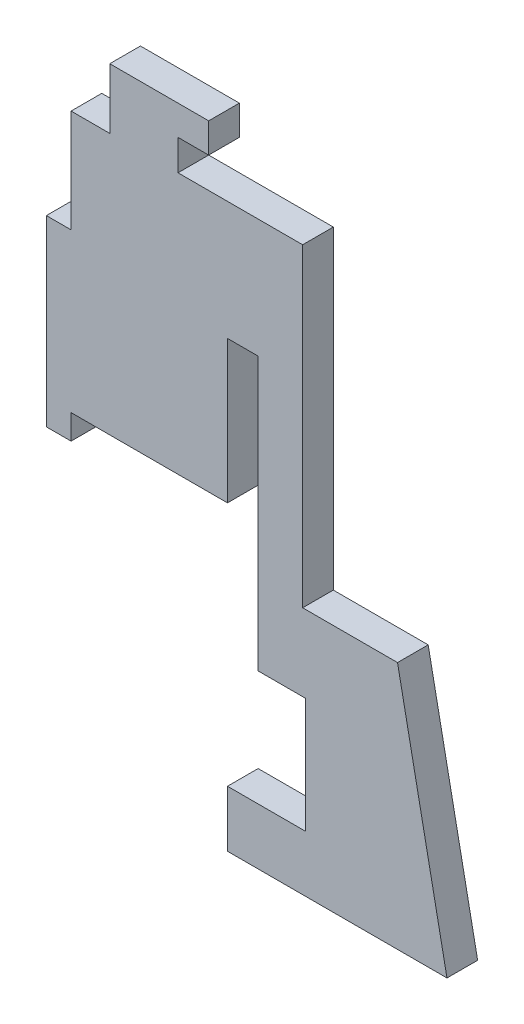
SolidWorks part; units mm, degrees
ref_plane "Front Plane" through (0, 0, 0) normal (0, 0, 1) x (1, 0, 0)
ref_plane "Top Plane" through (0, 0, 0) normal (0, 1, 0) x (1, 0, 0)
ref_plane "Right Plane" through (0, 0, 0) normal (1, 0, 0) x (0, 0, -1)
sketch "Sketch1" plane through (0, 0, 0) normal (0, 0, 1) x (1, 0, 0)
  line L0 (-72.5, 31.1) -> (-70, 31.1)
  line L1 (-54.19, 8.7934) -> (-54.19, 3.1)
  line L2 (-72.5, 31.1) -> (-72.5, 49.6)
  line L3 (-70, 60) -> (-66.09, 60)
  line L4 (-54.19, 33.6) -> (-54.19, 48)
  line L5 (-70, 31.1) -> (-70, 33.6)
  line L6 (-70, 33.6) -> (-54.19, 33.6)
  line L7 (-59.19, 63.1) -> (-56.09, 63.1)
  line L8 (-59.19, 60) -> (-46.59, 60)
  line L9 (-70, 60) -> (-70, 49.6)
  line L10 (-66.09, 60) -> (-66.09, 66.1)
  line L11 (-66.09, 66.1) -> (-56.09, 66.1)
  line L12 (-59.19, 60) -> (-59.19, 63.1)
  line L13 (-70, 49.6) -> (-72.5, 49.6)
  line L14 (-37, 28.2166) -> (-32, 3.1)
  line L15 (-32, 3.1) -> (-54.19, 3.1)
  line L16 (-51.09, 20.4368) -> (-46.3195, 20.4368)
  line L17 (-46.3195, 20.4368) -> (-46.3195, 8.7934)
  line L18 (-37, 28.2166) -> (-46.59, 28.2166)
  line L19 (-46.3195, 8.7934) -> (-54.19, 8.7934)
  line L20 (-46.59, 28.2166) -> (-46.59, 60)
  line L21 (-54.19, 48) -> (-51.09, 48)
  line L22 (-51.09, 48) -> (-51.09, 20.4368)
  line L23 (-51.09, 48) -> (-54.19, 48) construction
  line L24 (-56.09, 63.1) -> (-56.09, 66.1)
  line L25 (-59.19, 60) -> (-59.19, 63.1) construction
  line L26 (-69.19, 63.1) -> (-59.19, 63.1) construction
  dimension "D1" = 2.5
  dimension "D4" = 3
  dimension "D5" = 16
extrude "Boss-Extrude1" add sketch "Sketch1" along normal up to vertex (1.55 mm away) and the other way up to vertex (1.55 mm away)
